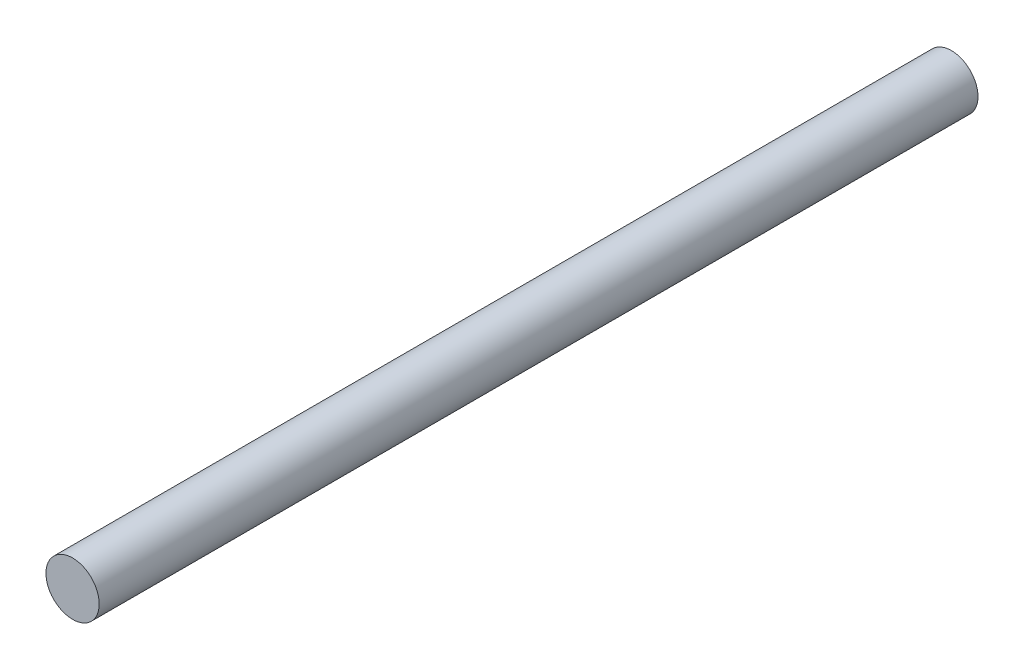
SolidWorks part; units mm, degrees
material "Plain Carbon Steel"
ref_plane "Front Plane" through (0, 0, 0) normal (0, 0, 1) x (1, 0, 0)
ref_plane "Top Plane" through (0, 0, 0) normal (0, 1, 0) x (1, 0, 0)
ref_plane "Right Plane" through (0, 0, 0) normal (1, 0, 0) x (0, 0, -1)
sketch "Sketch1" plane through (0, 0, 0) normal (0, 0, 1) x (1, 0, 0)
  circle A0 centre (0, 0) radius 2
extrude "Boss-Extrude1" add sketch "Sketch1" along normal blind 66
cosmetic thread "Cosmetic Thread1" parameters "D1"=8, "D2"=3.22
cosmetic thread "Cosmetic Thread2" parameters "D1"=8, "D2"=3.22
ref_plane "Plane1" [suppressed] through (0, 0, 25) normal (0, 0, 1) x (1, 0, 0)
ref_plane "Plane2" through (0, 0, 33) normal (0, 0, -1) x (-1, 0, 0)
